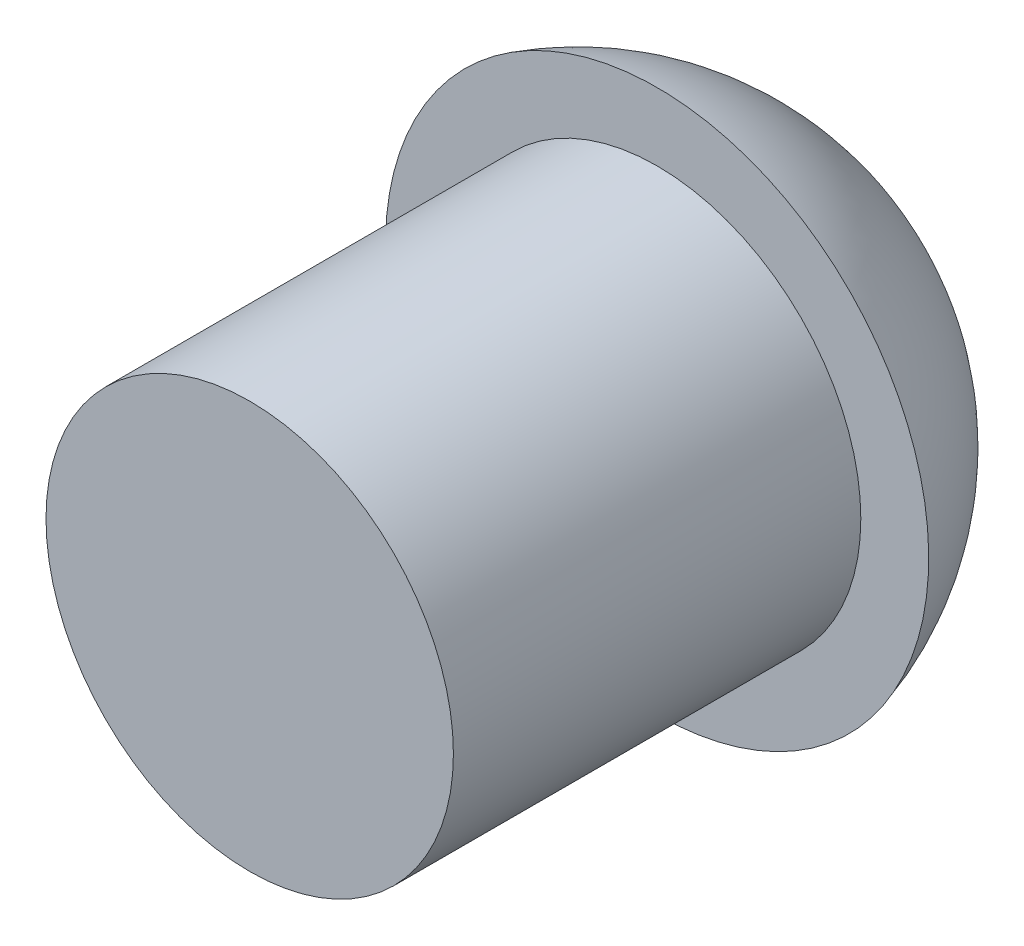
SolidWorks part; units mm, degrees
ref_plane "Front Plane" through (0, 0, 0) normal (0, 0, 1) x (1, 0, 0)
ref_plane "Top Plane" through (0, 0, 0) normal (0, 1, 0) x (1, 0, 0)
ref_plane "Right Plane" through (0, 0, 0) normal (1, 0, 0) x (0, 0, -1)
sketch "Sketch1" plane through (0, 0, 0) normal (0, 0, 1) x (1, 0, 0)
  circle A0 centre (0, 0) radius 3
  dimension "D1" = 6
extrude "Boss-Extrude1" add sketch "Sketch1" along normal blind 6
sketch "Sketch2" plane through (0, 0, 0) normal (0, 0, -1) x (-1, 0, 0)
  line L0 (-3, 0) -> (3, 0) construction
  circle A0 centre (0, 0) radius 3 construction
  point P5 (0, 0)
ref_plane "Plane1" through (0, 0, 0) normal (-1, 0, 0) x (0, 0, 1)
sketch "Sketch4" plane through (0, 0, 0) normal (-1, 0, 0) x (0, 0, 1)
  line L0 (0, -4) -> (0, 0)
  line L1 (0, 0) -> (-3, 0)
  line L2 (0, -3) -> (6, -3) construction
  line L3 (0, 3) -> (0, -3) construction
  arc A0 (-3, 0) -> (0, -4) centre (1.1667, 0) ccw
  point P10 (-3, 0)
  dimension "D1" = 1
  dimension "D2" = 3
revolve "Revolve1" add sketch "Sketch4" angle 360 about L1
ref_plane "Plane2" through (0, 0, -3) normal (0, 0, 1) x (1, 0, 0)
sketch "Sketch5" plane through (0, 0, -3) normal (0, 0, 1) x (1, 0, 0)
  line L0 (0, 1.8112) -> (1.4142, 0.397)
  line L1 (0, 2.2) -> (0, -2.2) construction
  line L2 (1.4142, 0.397) -> (0.6642, 0.397)
  line L3 (0.6642, 0.397) -> (0.6642, -1.603)
  line L4 (0.6642, -1.603) -> (-0.6642, -1.603)
  line L5 (0, 1.8112) -> (-1.4142, 0.397)
  line L6 (-1.4142, 0.397) -> (-0.6642, 0.397)
  line L7 (-0.6642, 0.397) -> (-0.6642, -1.603)
  circle A0 centre (0, 0) radius 4 construction
  point P10 (0, -1.603)
  dimension "D1" = 45
  dimension "D2" = 2
  dimension "D3" = 2
  dimension "D4" = 0.75
  dimension "D5" = 1.603
extrude "Cut-Extrude1" cut sketch "Sketch5" along normal blind 1
